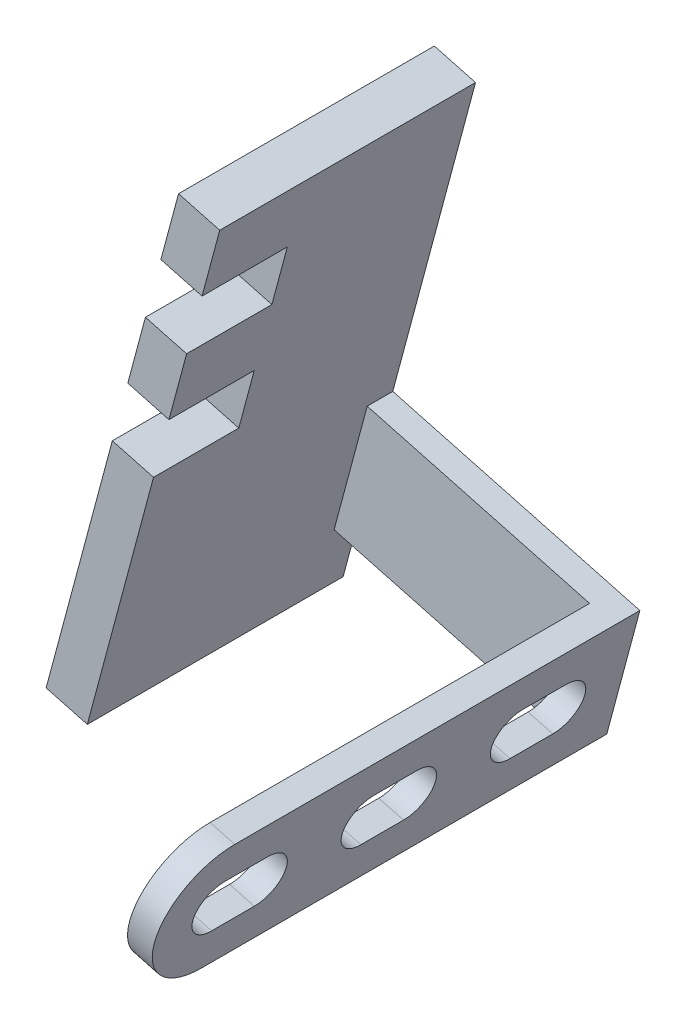
SolidWorks part; units mm, degrees
material "___"
ref_plane "Front Plane" through (0, 0, 0) normal (0, 0, 1) x (1, 0, 0)
ref_plane "Top Plane" through (0, 0, 0) normal (0, 1, 0) x (1, 0, 0)
ref_plane "Right Plane" through (0, 0, 0) normal (1, 0, 0) x (0, 0, -1)
sketch "Sketch2" plane through (0, 0, 0) normal (0, 0, 1) x (1, 0, 0)
  line L0 (0, 0) -> (0, 542.6218) construction
  line L1 (-9.6593, 2.5882) -> (0, 0)
  line L2 (-9.6593, 2.5882) -> (21.399, 118.4993)
  line L3 (0, 0) -> (31.0583, 115.9111)
  line L4 (21.399, 118.4993) -> (31.0583, 115.9111)
  line L5 (0, 0) -> (376.578, 0) construction
  point P3 (0, 0)
  dimension "D1" = 75
  dimension "D2" = 120
  dimension "D3" = 10
extrude "Boss-Extrude1" add sketch "Sketch2" along normal mid plane 60 contours L1 L2 L4 L3
sketch "Sketch3" plane through (0, 0, 0) normal (0.9659, -0.2588, 0) x (0, 0, -1)
  line L0 (-30, 0) -> (-30, 120) construction
  line L1 (-30, 104) -> (-10, 104)
  line L2 (-30, 104) -> (-30, 90)
  line L3 (-30, 90) -> (-10, 90)
  line L4 (-10, 104) -> (-10, 90)
  line L5 (-30, 120) -> (30, 120) construction
  line L6 (-30, 74) -> (-10, 74)
  line L7 (-30, 74) -> (-30, 60)
  line L8 (-30, 60) -> (-10, 60)
  line L9 (-10, 74) -> (-10, 60)
  dimension "D1" = 16
  dimension "D2" = 14
  dimension "D3" = 16
  dimension "D4" = 14
  dimension "D5" = 20
extrude "Cut-Extrude1" cut sketch "Sketch3" against normal blind 60
ref_plane "Plane1" through (7.7646, 28.9778, 0) normal (-0.2588, -0.9659, 0) x (-0.9659, 0.2588, 0)
sketch "Sketch5" plane through (7.7646, 28.9778, 0) normal (-0.2588, -0.9659, 0) x (-0.9659, 0.2588, 0)
  line L0 (0, 24) -> (-54, 24)
  line L1 (-54, 24) -> (-54, -65)
  line L2 (-54, -65) -> (-60, -65)
  line L3 (-60, -65) -> (-60, 30)
  line L4 (-60, 30) -> (0, 30)
  line L5 (0, 30) -> (0, 24)
  line L6 (0, -10) -> (0, -30) construction
  point P4 (0, 0)
  point P7 (-5.9324, 24)
  dimension "D1" = 95
  dimension "D2" = 60
  dimension "D3" = 6
  dimension "D4" = 6
extrude "Boss-Extrude2" add sketch "Sketch5" along normal mid plane 30
sketch "Sketch6" plane through (57.9555, -15.5291, 0) normal (0.9659, -0.2588, 0) x (0, 0, -1)
  line L1 (-65, 15) -> (-65, 45) construction
  line L2 (-65, 45) -> (-65, 15)
  arc A0 (-65, 45) -> (-65, 15) centre (-65, 30) ccw
extrude "Boss-Extrude3" add sketch "Sketch6" against normal up to surface (6 mm away) up to face at (59.9246, 15.0015, 20.5)
sketch "Sketch7" plane through (57.9555, -15.5291, 0) normal (0.9659, -0.2588, 0) x (0, 0, -1)
  line L0 (-65, 30) -> (-55, 30) construction
  line L1 (-65, 36) -> (-55, 36)
  line L2 (-65, 24) -> (-55, 24)
  line L3 (-65, 30) -> (-80, 30) construction
  line L4 (-30, 30) -> (-20, 30) construction
  line L5 (-30, 36) -> (-20, 36)
  line L6 (-30, 24) -> (-20, 24)
  line L7 (5, 30) -> (15, 30) construction
  line L8 (5, 36) -> (15, 36)
  line L9 (5, 24) -> (15, 24)
  line L10 (30, 15) -> (30, 45) construction
  arc A0 (-65, 36) -> (-65, 24) centre (-65, 30) ccw
  arc A1 (-55, 24) -> (-55, 36) centre (-55, 30) ccw
  arc A2 (-65, 45) -> (-65, 15) centre (-65, 30) ccw construction
  arc A3 (-30, 36) -> (-30, 24) centre (-30, 30) ccw
  arc A4 (-20, 24) -> (-20, 36) centre (-20, 30) ccw
  arc A5 (5, 36) -> (5, 24) centre (5, 30) ccw
  arc A6 (15, 24) -> (15, 36) centre (15, 30) ccw
  point P2 (-60, 30)
  point P15 (-25, 30)
  point P21 (10, 30)
  point P29 (5, 30)
  point P30 (15, 33.1948)
  dimension "D2" = 6
  dimension "D4" = 6
  dimension "D1" = 10
  dimension "D3" = 25
  dimension "D5" = 15
  dimension "D7" = 50
extrude "Cut-Extrude2" cut sketch "Sketch7" against normal blind 30
